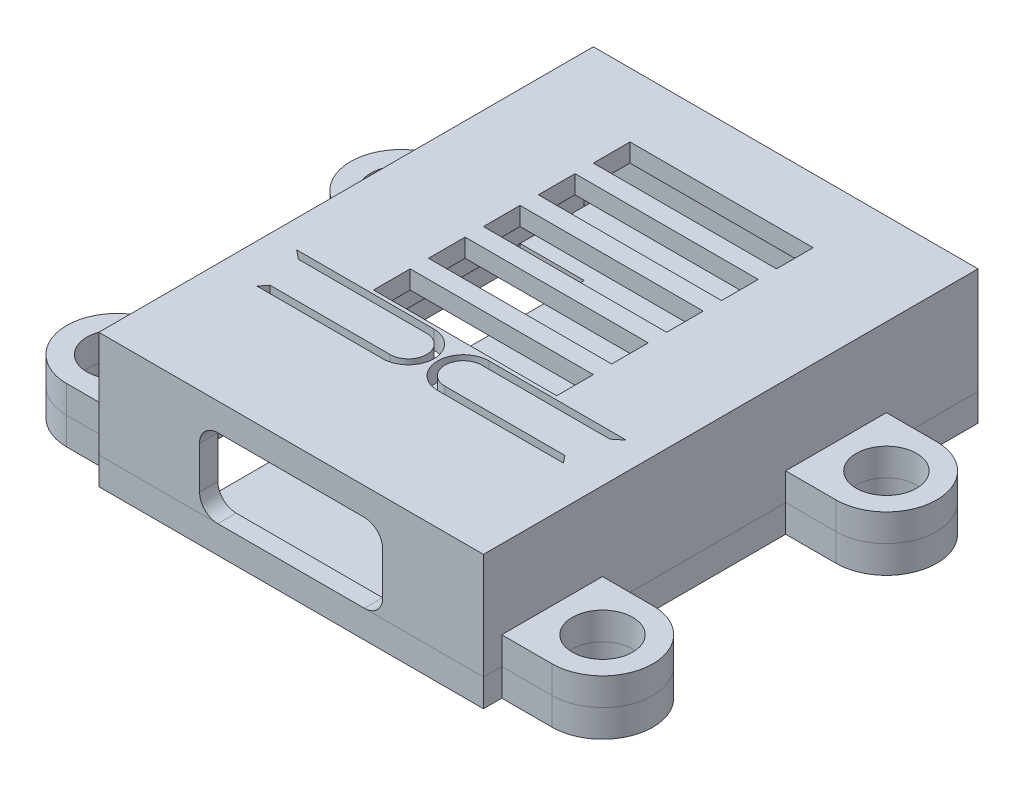
SolidWorks part; units mm, degrees
ref_plane "前视基准面" through (0, 0, 0) normal (0, 0, 1) x (1, 0, 0)
ref_plane "上视基准面" through (0, 0, 0) normal (0, 1, 0) x (1, 0, 0)
ref_plane "右视基准面" through (0, 0, 0) normal (1, 0, 0) x (0, 0, -1)
sketch "草图1" plane through (0, 0, 0) normal (0, -1, 0) x (1, 0, 0)
  line L0 (-9, 12) -> (-9, -8) construction
  line L1 (-9.5, 12.5) -> (9.5, 12.5)
  line L2 (-9.5, 12.5) -> (-9.5, -12.5)
  line L3 (-9.5, -12.5) -> (9.5, -12.5)
  line L4 (9.5, 12.5) -> (9.5, -12.5)
  line L5 (9, -8) -> (9, 12) construction
  line L6 (9, -12) -> (-9, -12) construction
  line L7 (-6.5, 12) -> (6.5, 12) construction
  dimension "D1" = 0.5
  dimension "D2" = 0.5
  dimension "D3" = 0.5
  dimension "D4" = 0.5
extrude "拉伸-薄壁1" add sketch "草图1" against normal offset from surface (6.3 mm away) 2 thin thin type one direction wall 1
sketch "草图2" plane through (0, 0, 13.5) normal (0, 0, 1) x (1, 0, 0)
  line L0 (-4, 0.5) -> (4, 0.5)
  line L1 (5, 1.5) -> (5, 3.8)
  line L2 (4, 4.8) -> (-4, 4.8)
  line L3 (-5, 3.8) -> (-5, 1.5)
  line L4 (-4.5, 4.3) -> (4.5, 4.3) construction
  line L5 (4.5, 4.3) -> (4.5, 1) construction
  line L6 (-4.5, 1) -> (4.5, 1) construction
  line L7 (-4.5, 4.3) -> (-4.5, 1) construction
  arc A4 (-5, 1.5) -> (-4, 0.5) centre (-4, 1.5) ccw
  arc A5 (4, 0.5) -> (5, 1.5) centre (4, 1.5) ccw
  arc A6 (4, 4.8) -> (5, 3.8) centre (4, 3.8) cw
  arc A7 (-4, 4.8) -> (-5, 3.8) centre (-4, 3.8) ccw
  dimension "D3" = 0.5
  dimension "D4" = 1
  dimension "D1" = 0.5
  dimension "D2" = 0.5
  dimension "D5" = 0.5
extrude "切除-拉伸1" cut sketch "草图2" against normal up to next
sketch "草图3" plane through (0, 0, 0) normal (0, -1, 0) x (1, 0, 0)
  line L1 (-10.5, 13.5) -> (10.5, 13.5)
  line L2 (-10.5, 13.5) -> (-10.5, -13.5)
  line L3 (-10.5, -13.5) -> (10.5, -13.5)
  line L4 (10.5, 13.5) -> (10.5, -13.5)
extrude "凸台-拉伸1" add sketch "草图3" along normal blind 1
sketch "草图4" plane through (0, -1, 0) normal (0, -1, 0) x (1, 0, 0)
  line L0 (-6.5, 12) -> (-9, 12) construction
  line L1 (-9.5, 12.5) -> (-6, 12.5)
  line L2 (-9.5, 12.5) -> (-9.5, -8.5)
  line L3 (-9.5, -8.5) -> (-6, -8.5)
  line L4 (-6, 12.5) -> (-6, -8.5)
  line L5 (6, 12.5) -> (9.5, 12.5)
  line L6 (6, 12.5) -> (6, -8.5)
  line L7 (6, -8.5) -> (9.5, -8.5)
  line L8 (9.5, 12.5) -> (9.5, -8.5)
  line L9 (-6.5, -8) -> (-6.5, 12) construction
  line L10 (-9, 12) -> (-9, -8) construction
  line L11 (-9, -8) -> (-6.5, -8) construction
  line L12 (9, 12) -> (6.5, 12) construction
  line L13 (9, -8) -> (9, 12) construction
  line L14 (6.5, 12) -> (6.5, -8) construction
  line L15 (6.5, -8) -> (9, -8) construction
  dimension "D1" = 0.5
  dimension "D2" = 0.5
  dimension "D3" = 0.5
  dimension "D4" = 0.5
  dimension "D5" = 0.5
  dimension "D6" = 0.5
  dimension "D7" = 0.5
  dimension "D8" = 0.5
extrude "切除-拉伸2" cut sketch "草图4" against normal up to next
sketch "草图5" plane through (0, -1, 0) normal (0, -1, 0) x (1, 0, 0)
  line L0 (0, 0) -> (0, 15.8133) construction
  line L1 (-6, 2) -> (16.2411, 2) construction
  line L2 (-6, -8.5) -> (-6, 12.5) construction
  line L3 (-10.5, 13.5) -> (-10.5, -13.5) construction
  line L4 (10.5, 13.5) -> (-10.5, 13.5) construction
  line L5 (-13.25, 12.5) -> (-10.5, 12.5)
  line L8 (-10.5, -8.5) -> (-10.5, -3)
  line L9 (-13.25, 7) -> (-10.5, 7)
  line L10 (-10.5, 12.5) -> (-10.5, 7)
  line L11 (-13.25, -3) -> (-10.5, -3)
  line L12 (-13.25, -8.5) -> (-10.5, -8.5)
  line L13 (13.25, -8.5) -> (10.5, -8.5)
  line L14 (13.25, -3) -> (10.5, -3)
  line L15 (10.5, 12.5) -> (10.5, 7)
  line L16 (13.25, 7) -> (10.5, 7)
  line L17 (10.5, -8.5) -> (10.5, -3)
  line L18 (13.25, 12.5) -> (10.5, 12.5)
  arc A0 (-13.25, 12.5) -> (-13.25, 7) centre (-13.25, 9.75) ccw
  arc A4 (-13.25, -8.5) -> (-13.25, -3) centre (-13.25, -5.75) cw
  arc A5 (13.25, -8.5) -> (13.25, -3) centre (13.25, -5.75) ccw
  arc A6 (13.25, 12.5) -> (13.25, 7) centre (13.25, 9.75) cw
  circle A7 centre (-13.25, 9.75) radius 1.7 construction
  dimension "D1" = 5.5
  dimension "D3" = 3.4
  dimension "D2" = 1
extrude "凸台-拉伸2" add sketch "草图5" against normal blind 3
sketch "草图6" plane through (0, 2, 0) normal (0, 1, 0) x (1, 0, 0)
  line L0 (-6, -2) -> (6, -2) construction
  line L1 (-6, -12.5) -> (-6, 8.5) construction
  line L2 (6, 8.5) -> (6, -12.5) construction
  line L3 (0, -2) -> (0, 6.897) construction
  circle A0 centre (-13.25, 5.75) radius 1.65
  circle A1 centre (-13.25, -9.75) radius 1.65
  circle A2 centre (13.25, -9.75) radius 1.65
  circle A3 centre (13.25, 5.75) radius 1.65
  dimension "D1" = 3.3
extrude "切除-拉伸3" cut sketch "草图6" against normal up to next
sketch "草图7" plane through (0, 6.3, 0) normal (0, 1, 0) x (1, 0, 0)
  line L1 (-9.5, 12.5) -> (9.5, 12.5)
  line L2 (-9.5, 12.5) -> (-9.5, -12.5)
  line L3 (-9.5, -12.5) -> (9.5, -12.5)
  line L4 (9.5, 12.5) -> (9.5, -12.5)
extrude "凸台-拉伸3" add sketch "草图7" against normal blind 1
sketch "草图8" plane through (0, 5.3, 0) normal (0, -1, 0) x (1, 0, 0)
  line L0 (9.5, -8.5) -> (9.5, 12.5) construction
  line L1 (-9.5, 12.5) -> (-6, 12.5)
  line L2 (-9.5, 12.5) -> (-9.5, -8.5)
  line L3 (-9.5, -8.5) -> (-6, -8.5)
  line L4 (-6, 12.5) -> (-6, -8.5)
  line L5 (6, 12.5) -> (9.5, 12.5)
  line L6 (6, 12.5) -> (6, -8.5)
  line L7 (6, -8.5) -> (9.5, -8.5)
  line L8 (9.5, 12.5) -> (9.5, -8.5)
extrude "凸台-拉伸4" add sketch "草图8" along normal offset from surface (1.8 mm away) 0.5 separate body
sketch "草图9" plane through (0, 6.3, 0) normal (0, 1, 0) x (1, 0, 0)
  line L0 (9, 12) -> (-9, 12) construction
  line L1 (-5, 10) -> (5, 10)
  line L2 (-5, 10) -> (-5, 8)
  line L3 (-5, 8) -> (5, 8)
  line L14 (0, 13.1121) -> (0, 0) construction
  line L20 (5, 10) -> (5, 8)
  line L21 (6, -12.5) -> (6, 8.5) construction
  line L22 (-5, 7) -> (5, 7)
  line L23 (-5, 7) -> (-5, 5)
  line L24 (-5, 5) -> (5, 5)
  line L25 (5, 7) -> (5, 5)
  line L26 (-5, 4) -> (5, 4)
  line L27 (-5, 4) -> (-5, 2)
  line L28 (-5, 2) -> (5, 2)
  line L29 (5, 4) -> (5, 2)
  line L30 (-5, 1) -> (5, 1)
  line L31 (-5, 1) -> (-5, -1)
  line L32 (-5, -1) -> (5, -1)
  line L33 (5, 1) -> (5, -1)
  line L34 (-5, -2) -> (5, -2)
  line L35 (-5, -2) -> (-5, -4)
  line L36 (-5, -4) -> (5, -4)
  line L37 (5, -2) -> (5, -4)
  line L38 (-5, 10) -> (-5, 7) construction
  dimension "D3" = 5
  dimension "D4" = 3
  dimension "D5" = 2
  dimension "D1" = 2
  dimension "D2" = 1
extrude "切除-拉伸6" cut sketch "草图9" against normal up to next (1 mm away)
sketch "草图10" plane through (0, 6.3, 0) normal (0, 1, 0) x (1, 0, 0)
  line L0 (0, 0) -> (0, -11.4327) construction
  line L1 (-1.5, -4.6) -> (-8.5, -4.6)
  line L3 (-8.05, -6.6) -> (-1.5, -6.6)
  line L4 (8.05, -6.6) -> (8.37, -7)
  line L5 (-4.5, -7.6) -> (-4.5, -15)
  line L6 (-4.5, -15) -> (4.5, -15)
  line L7 (4.5, -15) -> (4.5, -7.6)
  line L8 (4.5, -7.6) -> (-4.5, -7.6)
  line L9 (-4.5, -7.6) -> (-4.5, -15) construction
  line L10 (-4.5, -15) -> (4.5, -15) construction
  line L11 (4.5, -15) -> (4.5, -7.6) construction
  line L12 (4.5, -7.6) -> (-4.5, -7.6) construction
  line L13 (-1.5, -4.2) -> (-9, -4.2)
  line L15 (-8.37, -7) -> (-1.5, -7)
  line L16 (-8.5, -4.6) -> (-9, -4.2)
  line L17 (-8.05, -6.6) -> (-8.37, -7)
  line L18 (-10.5, -13.5) -> (-10.5, 13.5) construction
  line L19 (-9, -4.2) -> (-8.37, -7) construction
  line L20 (-8.5, -4.6) -> (-8.05, -6.6) construction
  line L21 (8.5, -4.6) -> (9, -4.2)
  line L22 (8.37, -7) -> (1.5, -7)
  line L23 (1.5, -4.2) -> (9, -4.2)
  line L24 (8.05, -6.6) -> (1.5, -6.6)
  line L25 (1.5, -4.6) -> (8.5, -4.6)
  line L26 (-8.37, -7) -> (-1.5, -7) construction
  circle A0 centre (-1.5, -5.6) radius 1 construction
  arc A2 (-1.5, -4.6) -> (-1.5, -6.6) centre (-1.5, -5.6) cw
  arc A3 (-1.5, -4.2) -> (-1.5, -7) centre (-1.5, -5.6) cw
  arc A4 (1.5, -4.2) -> (1.5, -7) centre (1.5, -5.6) ccw
  arc A5 (1.5, -4.6) -> (1.5, -6.6) centre (1.5, -5.6) ccw
  dimension "D1" = 0.5
  dimension "D2" = 0
  dimension "D3" = 1
  dimension "D4" = 2
  dimension "D5" = 1.5
  dimension "D7" = 2
  dimension "D6" = 0.4
extrude "切除-拉伸7" cut sketch "草图10" against normal up to next (1 mm away)
ref_plane "基准面1" through (0, 0.5, 0) normal (0, -1, 0) x (-1, 0, 0)
split "分割1" trim tools "基准面1" bodies to split 117 resulting bodies 118 119
